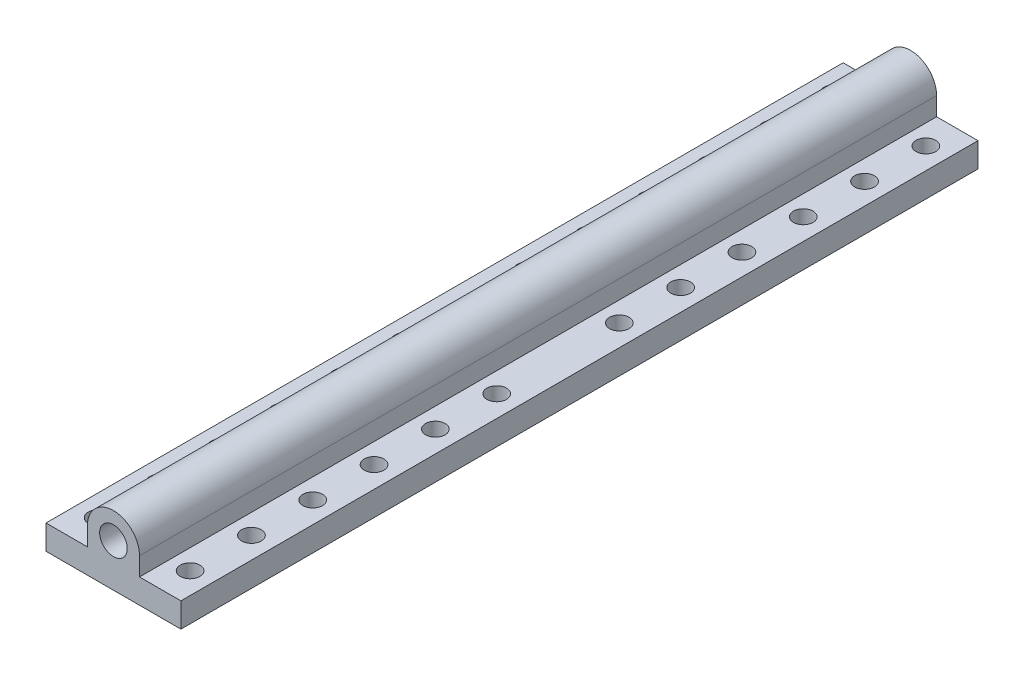
SolidWorks part; units mm, degrees
ref_plane "Ön Düzlem" through (0, 0, 0) normal (0, 0, 1) x (1, 0, 0)
ref_plane "Üst Düzlem" through (0, 0, 0) normal (0, 1, 0) x (1, 0, 0)
ref_plane "Sağ Düzlem" through (0, 0, 0) normal (1, 0, 0) x (0, 0, -1)
sketch "Çizim1" plane through (0, 0, 0) normal (0, 0, 1) x (1, 0, 0)
  line L0 (-9.7277, 0) -> (12.2723, 0)
  line L1 (12.2723, 0) -> (12.2723, 4)
  line L2 (12.2723, 4) -> (5.5223, 4)
  line L3 (-9.7277, 4) -> (-9.7277, 0)
  line L4 (-2.9777, 4) -> (-9.7277, 4)
  line L5 (-2.9777, 7) -> (-2.9777, 4)
  line L6 (5.5223, 7) -> (5.5223, 4)
  arc A0 (5.5223, 7) -> (-2.9777, 7) centre (1.2723, 7) ccw
  circle A1 centre (1.2723, 7) radius 2.25
  dimension "D5" = 8.5
  dimension "D6" = 4.5
  dimension "D1" = 4
  dimension "D2" = 4
  dimension "D3" = 22
extrude "Yükseklik-Ekstrüzyon1" add sketch "Çizim1" along normal blind 130
ref_plane "Düzlem1" through (0, 8.0851, 0) normal (0, 1, 0) x (1, 0, 0)
sketch "Çizim2" plane through (0, 8.0851, 0) normal (0, 1, 0) x (1, 0, 0)
  circle A0 centre (8.7723, -5) radius 1.6
  circle A1 centre (-6.2277, -5) radius 1.6
  circle A2 centre (-6.2277, -15) radius 1.6
  circle A3 centre (8.7723, -15) radius 1.6
  circle A4 centre (8.7723, -35) radius 1.6
  circle A5 centre (8.7723, -45) radius 1.6
  circle A6 centre (-6.2277, -35) radius 1.6
  circle A7 centre (-6.2277, -45) radius 1.6
  circle A8 centre (-6.2277, -25) radius 1.6
  circle A9 centre (8.7723, -25) radius 1.6
  circle A10 centre (-6.2277, -55) radius 1.6
  circle A11 centre (8.7723, -55) radius 1.6
  circle A12 centre (8.7723, -75) radius 1.6
  circle A13 centre (-6.2277, -75) radius 1.6
  circle A14 centre (8.7723, -105) radius 1.6
  circle A15 centre (-6.2277, -105) radius 1.6
  circle A16 centre (-6.2277, -85) radius 1.6
  circle A17 centre (-6.2277, -95) radius 1.6
  circle A18 centre (8.7723, -85) radius 1.6
  circle A19 centre (8.7723, -95) radius 1.6
  circle A20 centre (8.7723, -115) radius 1.6
  circle A21 centre (-6.2277, -115) radius 1.6
  circle A22 centre (-6.2277, -125) radius 1.6
  circle A23 centre (8.7723, -125) radius 1.6
  point P8 (0, 0)
  point P11 (0, 0)
  point P12 (0, 0)
  point P16 (0, 0)
  dimension "D1" = 3.2
  dimension "D2" = 3.2
  dimension "D3" = 3.2
  dimension "D4" = 3.2
  dimension "D5" = 3.2
  dimension "D6" = 3.2
  dimension "D7" = 3.2
  dimension "D8" = 3.2
extrude "Kes-Ekstrüzyon1" cut sketch "Çizim2" against normal blind 20
